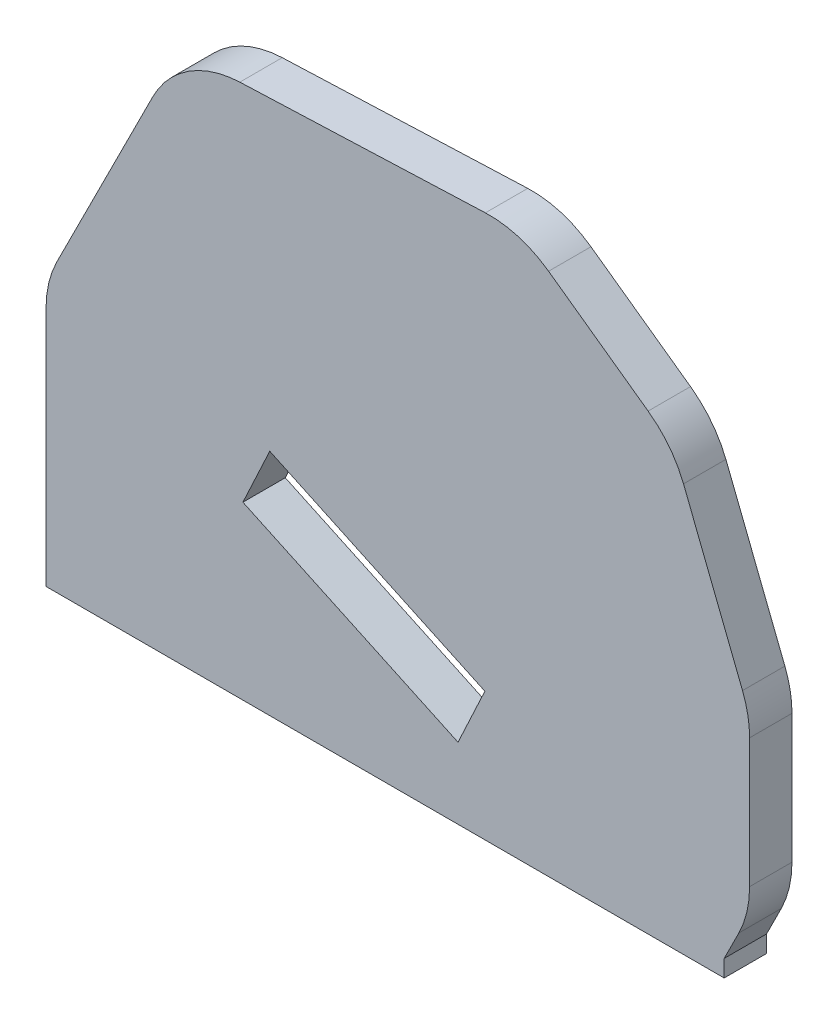
SolidWorks part; units mm, degrees
material "PBT General Purpose"
ref_plane "Front Plane" through (0, 0, 0) normal (0, 0, 1) x (1, 0, 0)
ref_plane "Top Plane" through (0, 0, 0) normal (0, 1, 0) x (1, 0, 0)
ref_plane "Right Plane" through (0, 0, 0) normal (1, 0, 0) x (0, 0, -1)
sketch "frame_outline" plane through (0, 0, 0) normal (0, 0, 1) x (1, 0, 0)
  line L0 (0, 0) -> (4, 0)
  line L1 (4, 0) -> (4, 0.1)
  line L2 (4, 0.1) -> (4.15, 0.4)
  line L3 (4.15, 0.4) -> (4.15, 1.4161)
  line L19 (4.15, 1.4161) -> (3.6952, 2.5687)
  line L20 (3.6952, 2.5687) -> (2.7971, 3.2123)
  line L21 (2.7971, 3.2123) -> (0.7894, 3.134)
  line L62 (0.7894, 3.134) -> (0, 1.5628)
  line L63 (0, 1.5628) -> (0, 0)
  line L64 (1.1613, 1.011) -> (2.4301, 0.4193)
  line L65 (1.1613, 1.011) -> (1.3198, 1.3509)
  line L66 (2.4301, 0.4193) -> (2.5886, 0.7592)
  line L67 (1.3198, 1.3509) -> (2.5886, 0.7592)
  line L68 (1.2405, 1.1809) -> (2.5094, 0.5893) construction
  dimension "D1" = 4
  dimension "D6" = 0.1
  dimension "D7" = 0.15
  dimension "D8" = 0.3
  dimension "D12" = 0.375
  dimension "D13" = 1.4
  dimension "D14" = 25
  dimension "D3" = 1.6
extrude "Boss-Extrude1" add sketch "frame_outline" along normal mid plane 0.25
fillet "Fillet1" radius 0.6 6 edges at (4.15, 0.4, 0) (4.15, 1.4161, 0) (3.6952, 2.5687, 0) (2.7971, 3.2123, 0) (0.7894, 3.134, 0) (0, 1.5628, 0)
equation "\"t\"= 0.25'thickness of the sheets"
equation "\"t_cf\" = 0.115'thickness of single carbon fiber layer"
equation "\"t_kapton\" = 0.025'thickness of single Kapton flex layer"
equation "\"t_fr4\" = 0.1'thickness of FR4 with copper layer"
equation "\"joint_flex\"= 0.1'Width of flextures gap"
equation "\"joint_flex_eff\"= 0.02'Width of flecture after castelation"
equation "\"joint_fold\"= 0.2'Width of folding joints for 90deg fold"
equation "\"gap_tolerance\"= 0.002'Width to have interfecence fit between carbon fiber inserts"
equation "\"assemble_angle\"= 90'Angle of assembly parts"
equation "\"D1@Boss-Extrude1\"=\"t\""
equation "\"D12@frame_outline\"=\"t\"*1.5"
equation "\"link_lift\"= 0.5'Actuation linkage amplification for the lift motion"
equation "\"link_swing\"= 0.45'Actuation linkage amplification for the swing motion"
